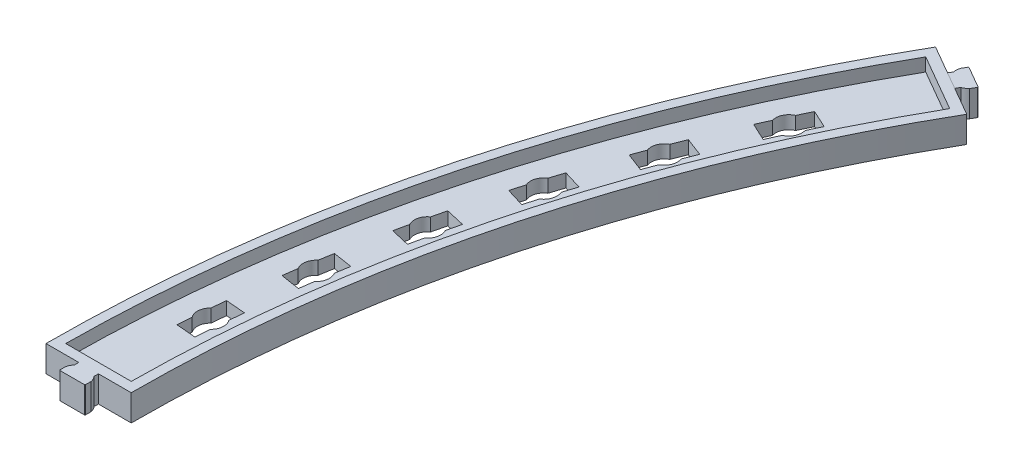
SolidWorks part; units mm, degrees
ref_plane "前视基准面" through (0, 0, 0) normal (0, 0, 1) x (1, 0, 0)
ref_plane "上视基准面" through (0, 0, 0) normal (0, 1, 0) x (1, 0, 0)
ref_plane "右视基准面" through (0, 0, 0) normal (1, 0, 0) x (0, 0, -1)
sketch "草图1" plane through (0, 0, 0) normal (0, 1, 0) x (1, 0, 0)
  line L0 (0, 0) -> (-201, 0) construction
  line L1 (0, 0) -> (-174.0711, 100.5) construction
  line L2 (-201, 0) -> (-214, 0)
  line L3 (-174.0711, 100.5) -> (-185.3294, 107)
  arc A0 (-174.0711, 100.5) -> (-201, 0) centre (0, 0) ccw
  arc A1 (-185.3294, 107) -> (-214, 0) centre (0, 0) ccw
  dimension "D2" = 402
  dimension "D3" = 428
  dimension "D1" = 30
extrude "凸台-拉伸1" add sketch "草图1" along normal blind 4
sketch "草图2" plane through (0, 4, 0) normal (0, 1, 0) x (1, 0, 0)
  line L2 (-214, 1.5) -> (-201, 1.5)
  line L3 (-212.4947, 1.5) -> (-202.4944, 1.5)
  line L5 (-174.8211, 99.201) -> (-186.0794, 105.701)
  line L6 (-176.1153, 99.9482) -> (-184.7758, 104.9483)
  arc A0 (-176.1153, 99.9482) -> (-202.4944, 1.5) centre (0, 0) ccw
  arc A1 (-184.7758, 104.9483) -> (-212.4947, 1.5) centre (0, 0) ccw
  dimension "D1" = 405
  dimension "D2" = 425
  dimension "D3" = 1.5
  dimension "D4" = 1.5
extrude "切除-拉伸1" cut sketch "草图2" against normal blind 2
sketch "草图3" plane through (0, 2, 0) normal (0, 1, 0) x (1, 0, 0)
  line L0 (0, 0) -> (-201, 0) construction
  line L1 (0, 0) -> (-194.1511, 52.0226) construction
  line L2 (0, 0) -> (-202.2398, 46.4254) construction
  line L3 (-194.1511, 52.0226) -> (-200.4296, 53.705) construction
  line L8 (-199.9658, 49.4944) -> (-202.8901, 50.1657)
  line L9 (-201.5319, 42.6719) -> (-204.4563, 43.3432)
  arc A0 (-174.0711, 100.5) -> (-201, 0) centre (0, 0) ccw construction
  circle A1 centre (0, 0) radius 207.5 construction
  arc A2 (-203.4006, 48.0541) -> (-203.9947, 45.4661) centre (-202.2398, 46.4254) ccw
  arc A3 (-201.0686, 44.8042) -> (-201.5319, 42.6719) centre (0, 0) ccw
  arc A4 (-203.9947, 45.4661) -> (-204.4563, 43.3432) centre (0, 0) ccw
  arc A5 (-201.0686, 44.8042) -> (-200.4788, 47.3735) centre (-202.2398, 46.4254) ccw
  arc A6 (-199.9658, 49.4944) -> (-200.4788, 47.3735) centre (0, 0) ccw
  arc A7 (-202.8901, 50.1657) -> (-203.4006, 48.0541) centre (0, 0) ccw
  dimension "D1" = 415
  dimension "D3" = 4
  dimension "D4" = 412
  dimension "D5" = 418
  dimension "D2" = 7.5
extrude "切除-拉伸2" cut sketch "草图3" against normal blind 2
pattern_circular "阵列(圆周)1" count 3 over 8 about axis through (0, 0, 0) along (0, 1, 0) of "切除-拉伸2"
pattern_circular "阵列(圆周)2" count 4 over 12 about axis through (0, 0, 0) along (0, 1, 0) of "切除-拉伸2"
sketch "草图4" plane through (0, 4, 0) normal (0, 1, 0) x (1, 0, 0)
  line L0 (-179.7003, 103.75) -> (-178.7003, 105.4821) construction
  line L1 (-174.0711, 100.5) -> (-185.3294, 107) construction
  line L2 (-178.7003, 105.4821) -> (-178.4503, 105.9151) construction
  line L3 (-176.7615, 104.9401) -> (-180.139, 106.8901)
  line L4 (-180.139, 106.8901) -> (-180.6112, 106.0722)
  line L5 (-178.4012, 103) -> (-180.9993, 104.5)
  line L6 (-180.9993, 104.5) -> (-180.6607, 105.0864)
  line L7 (-178.4012, 103) -> (-178.0627, 103.5864)
  line L8 (-176.7615, 104.9401) -> (-177.2337, 104.1222)
  arc A0 (-180.6112, 106.0722) -> (-180.6607, 105.0864) centre (-178.7003, 105.4821) ccw
  arc A1 (-177.2337, 104.1222) -> (-178.0627, 103.5864) centre (-178.7003, 105.4821) cw
  dimension "D7" = 2
  dimension "D1" = 2
  dimension "D2" = 0.5
  dimension "D5" = 1.95
  dimension "D6" = 1.5
extrude "凸台-拉伸2" add sketch "草图4" against normal blind 4 separate body
sketch "草图5" plane through (0, 4, 0) normal (0, 1, 0) x (1, 0, 0)
  line L0 (-207.5, 0) -> (-207.5, -2) construction
  line L1 (-214, 0) -> (-201, 0) construction
  line L2 (-207.5, -2) -> (-207.5, -2.5) construction
  line L3 (-206, 0) -> (-209, 0)
  line L4 (-209, 0) -> (-209, -0.6771)
  line L5 (-205.55, -2.5) -> (-209.45, -2.5)
  line L6 (-209.45, -2.5) -> (-209.45, -1.5556)
  line L7 (-205.55, -2.5) -> (-205.55, -1.5556)
  line L8 (-206, 0) -> (-206, -0.6771)
  arc A0 (-209, -0.6771) -> (-209.45, -1.5556) centre (-207.5, -2) ccw
  arc A1 (-206, -0.6771) -> (-205.55, -1.5556) centre (-207.5, -2) cw
  dimension "D5" = 2
  dimension "D1" = 2
  dimension "D2" = 0.5
  dimension "D3" = 1.5
  dimension "D4" = 1.95
extrude "凸台-拉伸3" add sketch "草图5" against normal blind 4
fillet "圆角1" radius 0.1 2 edges at (-180.139, 2, -106.8901) (-176.7615, 2, -104.9401)
fillet "圆角2" radius 0.1 2 edges at (-209.45, 2, 2.5) (-205.55, 2, 2.5)
